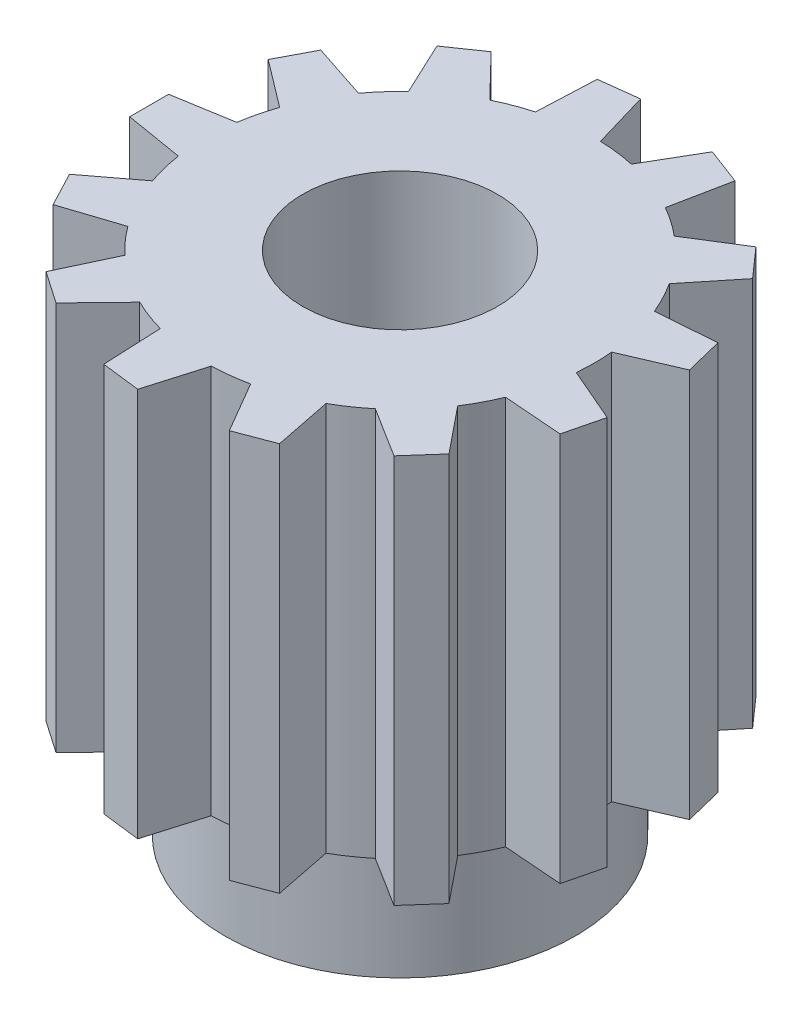
SolidWorks part; units mm, degrees
ref_plane "Front Plane" through (0, 0, 0) normal (0, 0, 1) x (1, 0, 0)
ref_plane "Top Plane" through (0, 0, 0) normal (0, 1, 0) x (1, 0, 0)
ref_plane "Right Plane" through (0, 0, 0) normal (1, 0, 0) x (0, 0, -1)
sketch "Sketch1" plane through (0, 0, 0) normal (0, 1, 0) x (1, 0, 0)
  circle A0 centre (0, 0) radius 2.5
  circle A1 centre (0, 0) radius 4.5
  dimension "D1" = 5
  dimension "D2" = 2
extrude "Boss-Extrude1" add sketch "Sketch1" along normal blind 3
sketch "Sketch2" plane through (0, 3, 0) normal (0, 1, 0) x (1, 0, 0)
  circle A0 centre (0, 0) radius 2.5 construction
  circle A1 centre (0, 0) radius 2.5
  circle A2 centre (0, 0) radius 5
  dimension "D1" = 10
extrude "Boss-Extrude2" add sketch "Sketch2" along normal blind 10
sketch "Sketch3" plane through (0, 13, 0) normal (0, 1, 0) x (1, 0, 0)
  line L0 (0, 0) -> (-5, 0) construction
  line L1 (-4.9434, -0.75) -> (-4.9434, 0.75)
  line L2 (-4.9434, -0.75) -> (-6.4434, -0.5)
  line L3 (-6.4434, -0.5) -> (-6.4434, 0.5)
  line L4 (-6.4434, 0.5) -> (-4.9434, 0.75)
  line L5 (-5.473, 3.4371) -> (-4.0286, 2.9614)
  line L6 (-4.7257, 1.6332) -> (-4.0286, 2.9614)
  line L7 (-4.7257, 1.6332) -> (-5.9377, 2.5517)
  line L8 (-5.9377, 2.5517) -> (-5.473, 3.4371)
  line L9 (-3.2488, 5.5869) -> (-2.191, 4.4944)
  line L10 (-3.4254, 3.6423) -> (-2.191, 4.4944)
  line L11 (-3.4254, 3.6423) -> (-4.0718, 5.0188)
  line L12 (-4.0718, 5.0188) -> (-3.2488, 5.5869)
  line L13 (-0.2803, 6.4567) -> (0.1487, 4.9978)
  line L14 (-1.3404, 4.817) -> (0.1487, 4.9978)
  line L15 (-1.3404, 4.817) -> (-1.273, 6.3362)
  line L16 (-1.273, 6.3362) -> (-0.2803, 6.4567)
  line L17 (2.7524, 5.8474) -> (2.4542, 4.3562)
  line L18 (1.0517, 4.8881) -> (2.4542, 4.3562)
  line L19 (1.0517, 4.8881) -> (1.8174, 6.202)
  line L20 (1.8174, 6.202) -> (2.7524, 5.8474)
  line L21 (5.1545, 3.8985) -> (4.1976, 2.7167)
  line L22 (3.2029, 3.8395) -> (4.1976, 2.7167)
  line L23 (3.2029, 3.8395) -> (4.4914, 4.647)
  line L24 (4.4914, 4.647) -> (5.1545, 3.8985)
  line L25 (6.3759, 1.0565) -> (4.9793, 0.4548)
  line L26 (4.6203, 1.9112) -> (4.9793, 0.4548)
  line L27 (4.6203, 1.9112) -> (6.1365, 2.0275)
  line L28 (6.1365, 2.0275) -> (6.3759, 1.0565)
  line L29 (6.1365, -2.0275) -> (4.6203, -1.9112)
  line L30 (4.9793, -0.4548) -> (4.6203, -1.9112)
  line L31 (4.9793, -0.4548) -> (6.3759, -1.0565)
  line L32 (6.3759, -1.0565) -> (6.1365, -2.0275)
  line L33 (4.4914, -4.647) -> (3.2029, -3.8395)
  line L34 (4.1976, -2.7167) -> (3.2029, -3.8395)
  line L35 (4.1976, -2.7167) -> (5.1545, -3.8985)
  line L36 (5.1545, -3.8985) -> (4.4914, -4.647)
  line L37 (1.8174, -6.202) -> (1.0517, -4.8881)
  line L38 (2.4542, -4.3562) -> (1.0517, -4.8881)
  line L39 (2.4542, -4.3562) -> (2.7524, -5.8474)
  line L40 (2.7524, -5.8474) -> (1.8174, -6.202)
  line L41 (-1.273, -6.3362) -> (-1.3404, -4.817)
  line L42 (0.1487, -4.9978) -> (-1.3404, -4.817)
  line L43 (0.1487, -4.9978) -> (-0.2803, -6.4567)
  line L44 (-0.2803, -6.4567) -> (-1.273, -6.3362)
  line L45 (-4.0718, -5.0188) -> (-3.4254, -3.6423)
  line L46 (-2.191, -4.4944) -> (-3.4254, -3.6423)
  line L47 (-2.191, -4.4944) -> (-3.2488, -5.5869)
  line L48 (-3.2488, -5.5869) -> (-4.0718, -5.0188)
  line L49 (-5.9377, -2.5517) -> (-4.7257, -1.6332)
  line L50 (-4.0286, -2.9614) -> (-4.7257, -1.6332)
  line L51 (-4.0286, -2.9614) -> (-5.473, -3.4371)
  line L52 (-5.473, -3.4371) -> (-5.9377, -2.5517)
  line L53 (0, 0) -> (-4.9434, 0.75) construction
  circle A0 centre (0, 0) radius 5 construction
  point P0 (-4.9434, 0.75)
  point P8 (-6.4434, 0)
  point P9 (-4.9434, 0)
  point P12 (0, 0)
  dimension "D1" = 1.5
  dimension "D2" = 1
  dimension "D3" = 1.5
  dimension "D5" = 13
extrude "Boss-Extrude3" add sketch "Sketch3" against normal up to surface (10 mm away) up to face at (0, 3, 4.5)
equation "\"motor_diameter\"= 38mm"
equation "\"motor_length\"= 60mm"
equation "\"shaft_diameter\"= 5mm"
equation "\"shaft_length\"= 10mm"
equation "\"D1@Sketch2\"=\"planet_gear_diameter\""
equation "\"planet_gear_diameter\"= 10mm"
equation "\"solar_diameter\"= 40mm"
equation "\"solar_thickness\"= 10mm"
equation "\"D1@Sketch1\"=\"shaft_diameter\""
